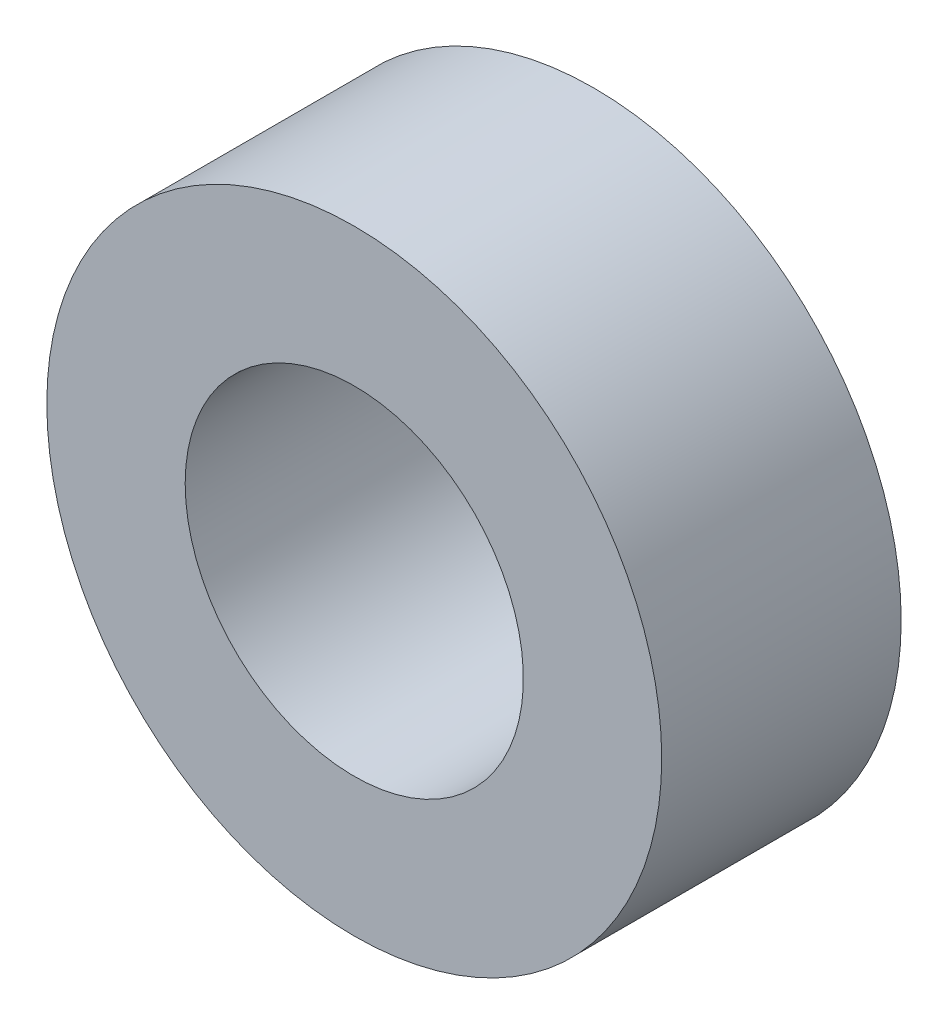
SolidWorks part; units mm, degrees
material "Nylon 101"
ref_plane "Front Plane" through (0, 0, 0) normal (0, 0, 1) x (1, 0, 0)
ref_plane "Top Plane" through (0, 0, 0) normal (0, 1, 0) x (1, 0, 0)
ref_plane "Right Plane" through (0, 0, 0) normal (1, 0, 0) x (0, 0, -1)
sketch "Sketch1" plane through (0, 0, 0) normal (0, 0, 1) x (1, 0, 0)
  circle A0 centre (0, 0) radius 9.525
  circle A1 centre (0, 0) radius 5.2387
  dimension "D1" = 19.05
  dimension "D2" = 10.4775
extrude "Boss-Extrude1" add sketch "Sketch1" along normal mid plane 7.4185
equation "\"D1@Boss-Extrude1\"=0.0625in+0.45mm/2"
